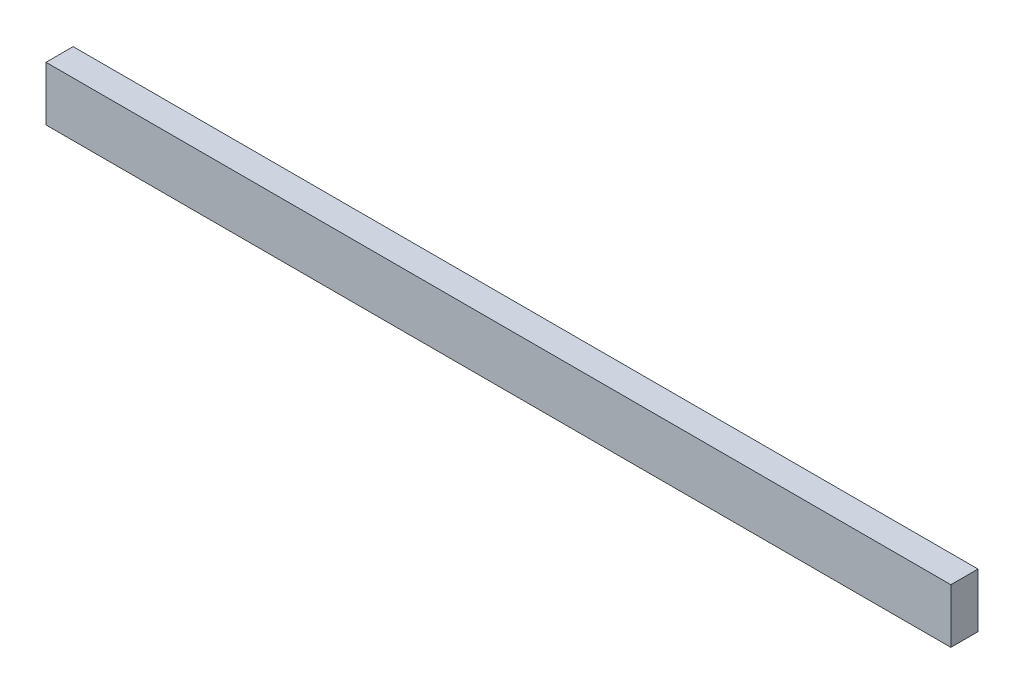
SolidWorks part; units mm, degrees
ref_plane "Front Plane" through (0, 0, 0) normal (0, 0, 1) x (1, 0, 0)
ref_plane "Top Plane" through (0, 0, 0) normal (0, 1, 0) x (1, 0, 0)
ref_plane "Right Plane" through (0, 0, 0) normal (1, 0, 0) x (0, 0, -1)
sketch "Sketch1" plane through (0, 0, 0) normal (0, 0, 1) x (1, 0, 0)
  line L1 (-50, 3) -> (50, 3)
  line L2 (-50, 3) -> (-50, -3)
  line L3 (-50, -3) -> (50, -3)
  line L4 (50, 3) -> (50, -3)
  line L5 (-50, 3) -> (50, -3) construction
  line L6 (-50, -3) -> (50, 3) construction
  point P0 (0, 0)
  dimension "D1" = 6
  dimension "D2" = 100
extrude "Boss-Extrude1" add sketch "Sketch1" along normal blind 3
